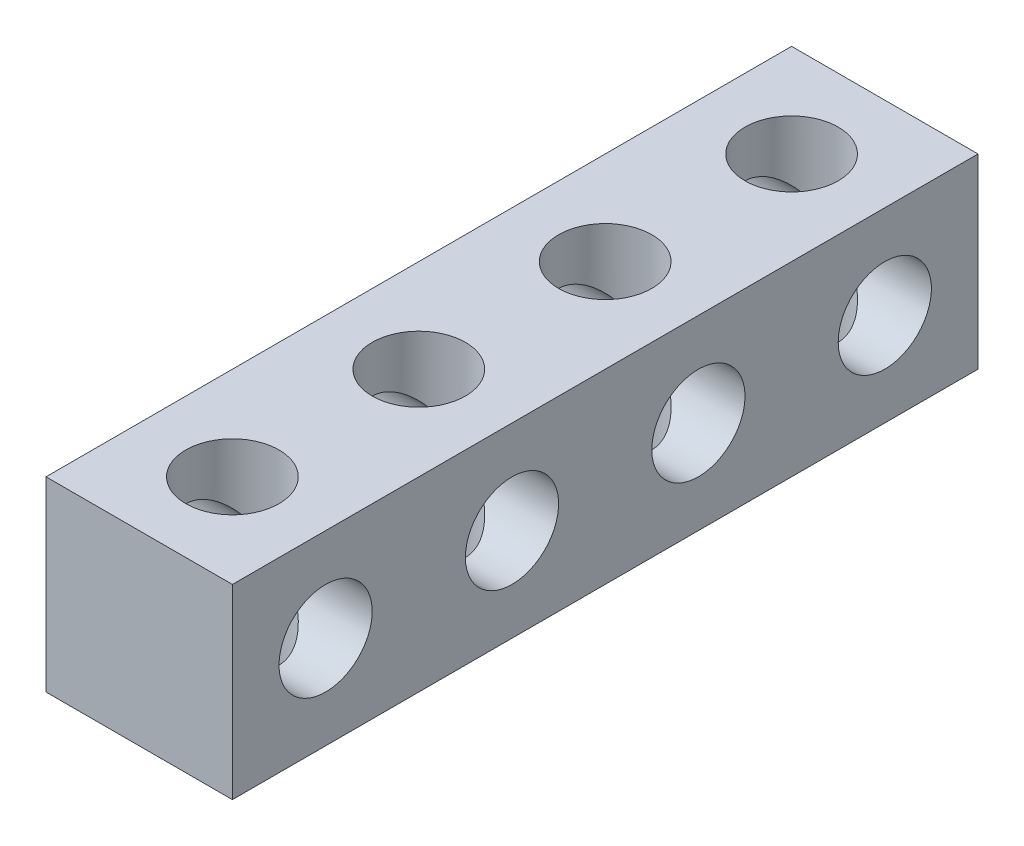
SolidWorks part; units mm, degrees
ref_plane "Front Plane" through (0, 0, 0) normal (0, 0, 1) x (1, 0, 0)
ref_plane "Top Plane" through (0, 0, 0) normal (0, 1, 0) x (1, 0, 0)
ref_plane "Right Plane" through (0, 0, 0) normal (1, 0, 0) x (0, 0, -1)
sketch "Sketch1" plane through (0, 0, 0) normal (0, 0, 1) x (1, 0, 0)
  line L1 (-6.35, -6.35) -> (6.35, -6.35)
  line L2 (-6.35, -6.35) -> (-6.35, 6.35)
  line L3 (-6.35, 6.35) -> (6.35, 6.35)
  line L4 (6.35, -6.35) -> (6.35, 6.35)
  line L5 (-6.35, -6.35) -> (6.35, 6.35) construction
  line L6 (-6.35, 6.35) -> (6.35, -6.35) construction
  point P0 (0, 0)
  dimension "D1" = 12.7
  dimension "D2" = 12.7
extrude "Boss-Extrude1" add sketch "Sketch1" along normal mid plane 50.8
sketch "Sketch2" plane through (0, 6.35, 0) normal (0, 1, 0) x (1, 0, 0)
  line L0 (6.35, 25.4) -> (-6.35, 25.4) construction
  circle A0 centre (0, 19.05) radius 3.175
  circle A1 centre (0, 6.35) radius 3.175
  circle A2 centre (0, -6.35) radius 3.175
  circle A3 centre (0, -19.05) radius 3.175
  circle A4 centre (0, -31.75) radius 3.175
  circle A5 centre (0, -44.45) radius 3.175
  dimension "D1" = 6.35
  dimension "D2" = 6.35
  dimension "D3" = 6
extrude "Cut-Extrude1" cut sketch "Sketch2" against normal through all
sketch "Sketch4" plane through (-6.35, 0, 0) normal (-1, 0, 0) x (0, 0, 1)
  line L0 (25.4, -6.35) -> (25.4, 6.35) construction
  circle A0 centre (19.05, 0) radius 3.175
  circle A1 centre (6.35, 0) radius 3.175
  circle A2 centre (-6.35, 0) radius 3.175
  circle A3 centre (-19.05, 0) radius 3.175
  circle A4 centre (-31.75, 0) radius 3.175
  circle A5 centre (-44.45, 0) radius 3.175
  dimension "D1" = 6.35
  dimension "D2" = 6.35
  dimension "D3" = 6
extrude "Cut-Extrude2" cut sketch "Sketch4" against normal through all
